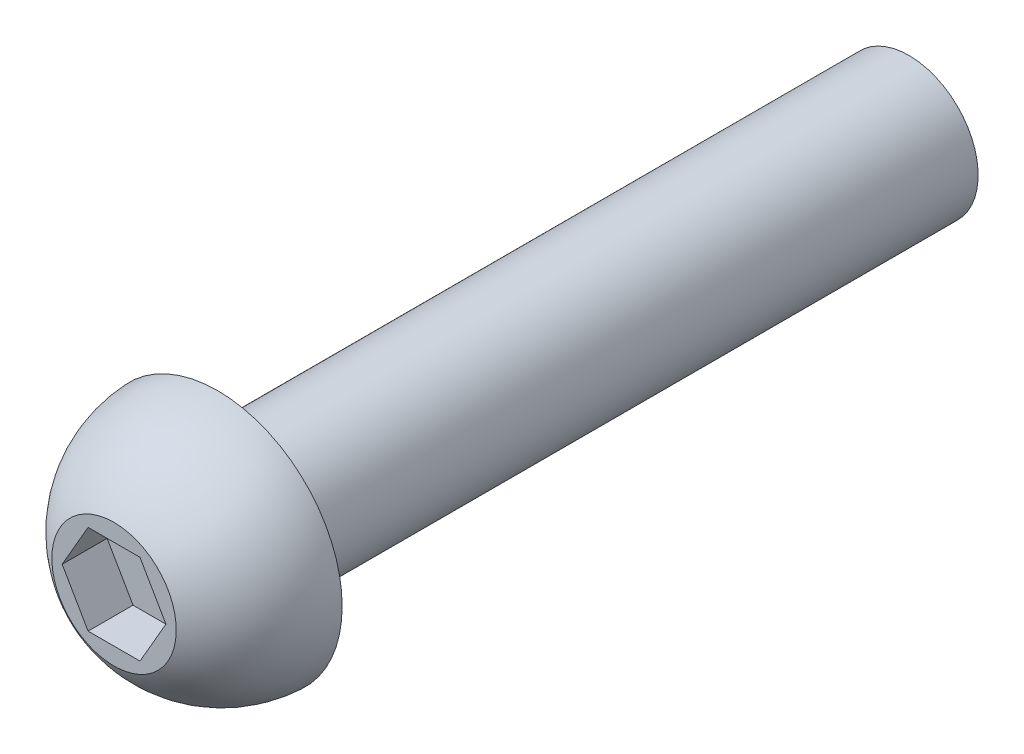
SolidWorks part; units mm, degrees
material "AISI 304"
ref_plane "前视基准面" through (0, 0, 0) normal (0, 0, 1) x (1, 0, 0)
ref_plane "上视基准面" through (0, 0, 0) normal (0, 1, 0) x (1, 0, 0)
ref_plane "右视基准面" through (0, 0, 0) normal (1, 0, 0) x (0, 0, -1)
sketch "草图1" plane through (0, 0, 0) normal (1, 0, 0) x (0, 0, -1)
  line L0 (0, 0) -> (-4.8165, 0) construction
  line L1 (0, 0) -> (0, 0.9)
  line L2 (1.5, 1.8) -> (1.5, 1)
  line L3 (1.5, 1) -> (11.5, 1)
  line L4 (11.5, 1) -> (11.5, 0)
  line L5 (0, 0) -> (11.5, 0)
  arc A0 (0, 0.9) -> (1.5, 1.8) centre (1.56, 0) cw
  dimension "头大径" = 3.6
  dimension "头厚" = 1.5
  dimension "直径" = 2
  dimension "长度" = 10
  dimension "头小径" = 1.8
revolve "旋转1" add sketch "草图1" angle 360 about L0
sketch "草图2" plane through (0, 0, 0) normal (0, 0, 1) x (1, 0, 0)
  line L1 (0.7506, 0) -> (0.3753, 0.65)
  line L2 (0.3753, 0.65) -> (-0.3753, 0.65)
  line L3 (-0.3753, 0.65) -> (-0.7506, 0)
  line L4 (-0.7506, 0) -> (-0.3753, -0.65)
  line L5 (-0.3753, -0.65) -> (0.3753, -0.65)
  line L6 (0.3753, -0.65) -> (0.7506, 0)
  circle A0 centre (0, 0) radius 0.65 construction
  dimension "槽宽" = 1.3
extrude "切除-拉伸1" cut sketch "草图2" against normal blind 0.65
chamfer "倒角1" [suppressed] distance 0.2 angle 45
equation "\"D1@切除-拉伸1\"=\"槽宽@草图2\"/2"
equation "\"D1@倒角1\"=\"直径@草图1\"*0.1"
